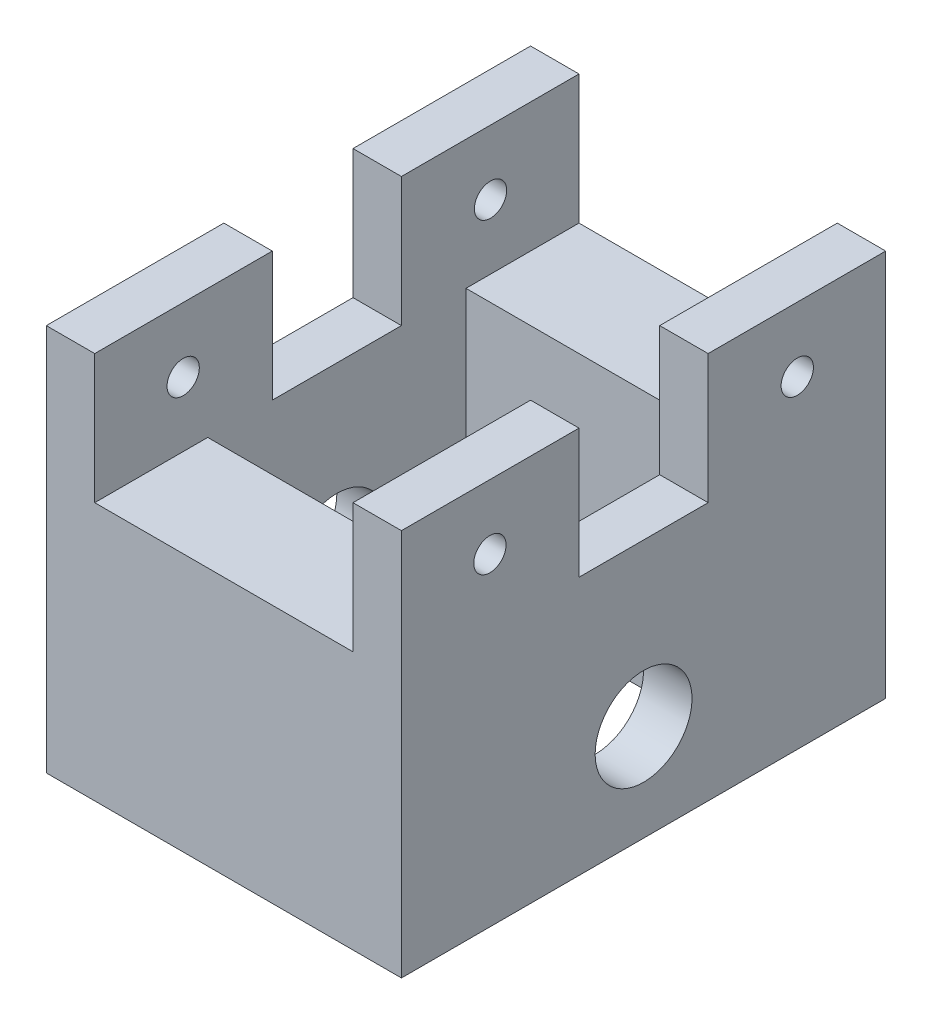
SolidWorks part; units mm, degrees
ref_plane "Front Plane" through (0, 0, 0) normal (0, 0, 1) x (1, 0, 0)
ref_plane "Top Plane" through (0, 0, 0) normal (0, 1, 0) x (1, 0, 0)
ref_plane "Right Plane" through (0, 0, 0) normal (1, 0, 0) x (0, 0, -1)
sketch "Sketch1" plane through (0, 0, 0) normal (0, 1, 0) x (1, 0, 0)
  line L1 (-50.8, -76.2) -> (50.8, -76.2)
  line L2 (-50.8, -76.2) -> (-50.8, 76.2)
  line L3 (-50.8, 76.2) -> (50.8, 76.2)
  line L4 (50.8, -76.2) -> (50.8, 76.2)
  line L5 (-50.8, -76.2) -> (50.8, 76.2) construction
  line L6 (-50.8, 76.2) -> (50.8, -76.2) construction
  point P0 (0, 0)
  dimension "D1" = 101.6
  dimension "D2" = 152.4
extrude "Extrude-Thin1" add sketch "Sketch1" along normal blind 152.4 thin
sketch "Sketch2" plane through (0, 152.4, 0) normal (0, 1, 0) x (1, 0, 0)
  line L0 (-69.85, -95.25) -> (69.85, -95.25) construction
  line L1 (-50.8, -76.2) -> (50.8, -76.2)
  line L2 (-50.8, -76.2) -> (-50.8, -95.25)
  line L3 (-50.8, -95.25) -> (50.8, -95.25)
  line L4 (50.8, -76.2) -> (50.8, -95.25)
ref_plane "Plane1" through (0, 101.6, 0) normal (0, 1, 0) x (1, 0, 0)
extrude "Cut-Extrude1" cut sketch "Sketch2" against normal up to surface (50.8 mm away)
sketch "Sketch5" plane through (0, 0, 95.25) normal (0, 0, 1) x (1, 0, 0)
  line L1 (-50.8, 152.4) -> (50.8, 152.4)
  line L2 (-50.8, 152.4) -> (-50.8, 101.6)
  line L3 (-50.8, 101.6) -> (50.8, 101.6)
  line L4 (50.8, 152.4) -> (50.8, 101.6)
extrude "Cut-Extrude5" cut sketch "Sketch5" against normal up to surface (190.5 mm away) up to face at (0, 76.2, -95.25)
sketch "Sketch6" plane through (-69.85, 0, 0) normal (-1, 0, 0) x (0, 0, 1)
  line L0 (0, 0) -> (0, 38.1)
  circle A0 centre (0, 38.1) radius 19.05
  dimension "D2" = 38.1
  dimension "D1" = 38.1
extrude "Cut-Extrude6" cut sketch "Sketch6" against normal through all both and the other way through all
sketch "Sketch7" plane through (69.85, 0, 0) normal (1, 0, 0) x (0, 0, -1)
  line L0 (0, 152.4) -> (0, 127) construction
  line L1 (-95.25, 152.4) -> (95.25, 152.4) construction
  line L2 (-60.452, 127) -> (60.452, 127) construction
  circle A1 centre (-60.452, 127) radius 6.35
  circle A2 centre (60.452, 127) radius 6.35
  point P8 (0, 127)
  dimension "D2" = 60.452
  dimension "D3" = 12.7
  dimension "D4" = 12.7
  dimension "D1" = 25.4
extrude "Cut-Extrude8" cut sketch "Sketch7" against normal through all
sketch "Sketch3" plane through (0, 0, 0) normal (0, -1, 0) x (1, 0, 0)
  line L0 (-69.85, -95.25) -> (-69.85, 95.25) construction
  line L1 (-50.8, 76.2) -> (-69.85, 76.2)
  line L2 (-50.8, 76.2) -> (-50.8, -50.8)
  line L3 (-50.8, -50.8) -> (-69.85, -50.8)
  line L4 (-69.85, 76.2) -> (-69.85, -50.8)
extrude "Cut-Extrude2" cut sketch "Sketch3" against normal up to surface (101.6 mm away)
ref_plane "Plane2" through (72.39, 0, 0) normal (1, 0, 0) x (0, 0, -1)
mirror "Mirror2" about plane through (72.39, 0, 0) normal (1, 0, 0) of bodies 103
sketch "Sketch4" plane through (72.39, 0, 0) normal (1, 0, 0) x (0, 0, -1)
  line L0 (95.25, 152.4) -> (-95.25, 152.4) construction
  line L1 (-144.5856, 152.4) -> (222.6561, 152.4)
  line L2 (-144.5856, 152.4) -> (-144.5856, -37.1296)
  line L3 (-144.5856, -37.1296) -> (222.6561, -37.1296)
  line L4 (222.6561, 152.4) -> (222.6561, -37.1296)
extrude "Cut-Extrude4" cut sketch "Sketch4" along normal up to surface (142.24 mm away) up to face at (214.63, 127, 54.102)
sketch "Sketch8" plane through (-69.85, 0, 0) normal (-1, 0, 0) x (0, 0, 1)
  line L7 (76.2, 0) -> (-95.25, 0)
  line L8 (76.2, 0) -> (76.2, 101.6)
  line L9 (76.2, 101.6) -> (-95.25, 101.6)
  line L10 (-95.25, 0) -> (-95.25, 101.6)
  dimension "D1" = 101.6
  dimension "D2" = 171.45
extrude "Boss-Extrude1" add sketch "Sketch8" against normal up to surface (19.05 mm away)
sketch "Sketch9" plane through (69.85, 0, 0) normal (1, 0, 0) x (0, 0, -1)
  circle A0 centre (0, 38.1) radius 19.05 construction
  circle A1 centre (0, 38.1) radius 19.05
extrude "Cut-Extrude9" cut sketch "Sketch9" against normal through all both
sketch "Sketch10" plane through (0, 0, 0) normal (0, -1, 0) x (1, 0, 0)
  line L0 (50.8, -50.8) -> (50.8, -76.2)
  line L1 (-50.8, 76.2) -> (50.8, 76.2)
  line L2 (-50.8, 76.2) -> (-50.8, 50.8)
  line L3 (-50.8, -76.2) -> (50.8, -76.2)
  line L4 (50.8, 76.2) -> (50.8, 50.8)
  line L5 (-50.8, -50.8) -> (50.8, -50.8)
  line L7 (-50.8, 50.8) -> (50.8, 50.8)
  line L11 (-50.8, -50.8) -> (-50.8, -76.2)
  point P6 (0, 0)
  dimension "D1" = 101.6
  dimension "D2" = 25.4
extrude "Boss-Extrude2" add sketch "Sketch10" against normal up to surface (101.6 mm away) up to face at (0, 101.6, 85.725)
sketch "Sketch11" plane through (0, 152.4, 0) normal (0, 1, 0) x (1, 0, 0)
  line L0 (-69.85, 95.25) -> (-69.85, -95.25) construction
  line L1 (69.85, -25.4) -> (-69.85, -25.4)
  line L2 (69.85, -25.4) -> (69.85, 25.4)
  line L3 (69.85, 25.4) -> (-69.85, 25.4)
  line L4 (-69.85, -25.4) -> (-69.85, 25.4)
  line L5 (69.85, -25.4) -> (-69.85, 25.4) construction
  line L6 (69.85, 25.4) -> (-69.85, -25.4) construction
  point P0 (0, 0)
  dimension "D1" = 50.8
extrude "Cut-Extrude10" cut sketch "Sketch11" against normal blind 50.8
